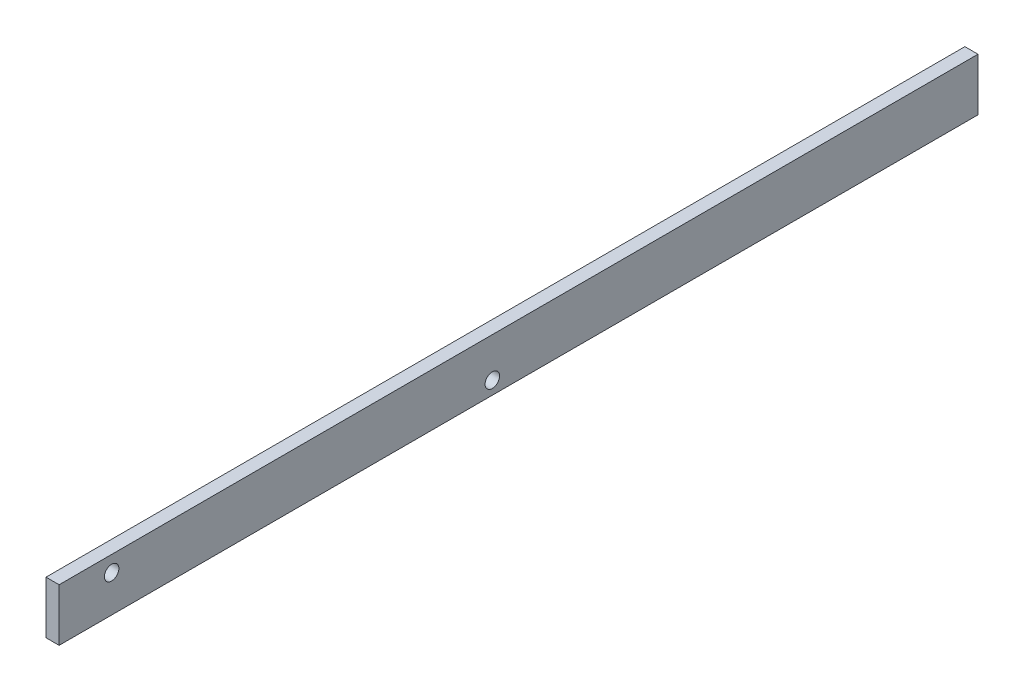
SolidWorks part; units mm, degrees
ref_plane "Front Plane" through (0, 0, 0) normal (0, 0, 1) x (1, 0, 0)
ref_plane "Top Plane" through (0, 0, 0) normal (0, 1, 0) x (1, 0, 0)
ref_plane "Right Plane" through (0, 0, 0) normal (1, 0, 0) x (0, 0, -1)
sketch "Sketch1" plane through (0, 0, 0) normal (0, 0, 1) x (1, 0, 0)
  line L1 (0, 0) -> (3.175, 0)
  line L2 (0, 0) -> (0, -12.7)
  line L3 (0, -12.7) -> (3.175, -12.7)
  line L4 (3.175, 0) -> (3.175, -12.7)
  dimension "D1" = 3.175
  dimension "D2" = 12.7
extrude "Boss-Extrude1" add sketch "Sketch1" along normal blind 222.25
sketch "Sketch2" plane through (3.175, 0, 0) normal (1, 0, 0) x (0, 0, -1)
  line L1 (-222.25, -12.7) -> (-222.25, 0) construction
  line L2 (-117.475, -6.35) -> (-117.475, 0)
  line L5 (-222.25, 0) -> (0, 0) construction
  circle A0 centre (-117.475, -9.525) radius 3.175 construction
  point P6 (-209.55, -3.81)
  point P8 (-117.475, -9.525)
  dimension "D3" = 6.35
  dimension "D4" = 104.775
  dimension "D5" = 6.35
  dimension "D1" = 12.7
  dimension "D2" = 3.81
hole_wizard "#6 (0.138) Diameter Hole1" positions "3DSketch1" profile "Sketch3" hole size "#6" standard "ANSI Inch" end condition through all
sketch3d "3DSketch1"
  point P2 (3.175, -3.81, 209.55)
  point P6 (3.175, 0, 196.85)
sketch "Sketch3" plane through (3.175, -3.81, 209.55) normal (0, 1, 0) x (0, 0, -1)
  line L0 (0, 0) -> (0, 3.175)
  line L1 (0, 3.175) -> (1.7526, 3.175)
  line L2 (1.7526, 3.175) -> (1.7526, 0)
  line L5 (1.7526, 0) -> (0, 0)
  line L11 (0, -6.35) -> (0, 107.95) construction
  dimension "Thru Hole Dia." = 3.5052
  dimension "Thru Hole Depth" = 3.175
hole_wizard "#6 (0.138) Diameter Hole3" positions "3DSketch3" profile "Sketch5" hole size "#6" standard "ANSI Inch" end condition through all
sketch3d "3DSketch3"
  point P0 (3.175, -9.525, 117.475)
sketch "Sketch5" plane through (3.175, -9.525, 117.475) normal (0, 1, 0) x (0, 0, -1)
  line L0 (0, 0) -> (0, 3.175)
  line L1 (0, 3.175) -> (1.7526, 3.175)
  line L2 (1.7526, 3.175) -> (1.7526, 0)
  line L5 (1.7526, 0) -> (0, 0)
  line L11 (0, -6.35) -> (0, 107.95) construction
  dimension "Thru Hole Dia." = 3.5052
  dimension "Thru Hole Depth" = 3.175
